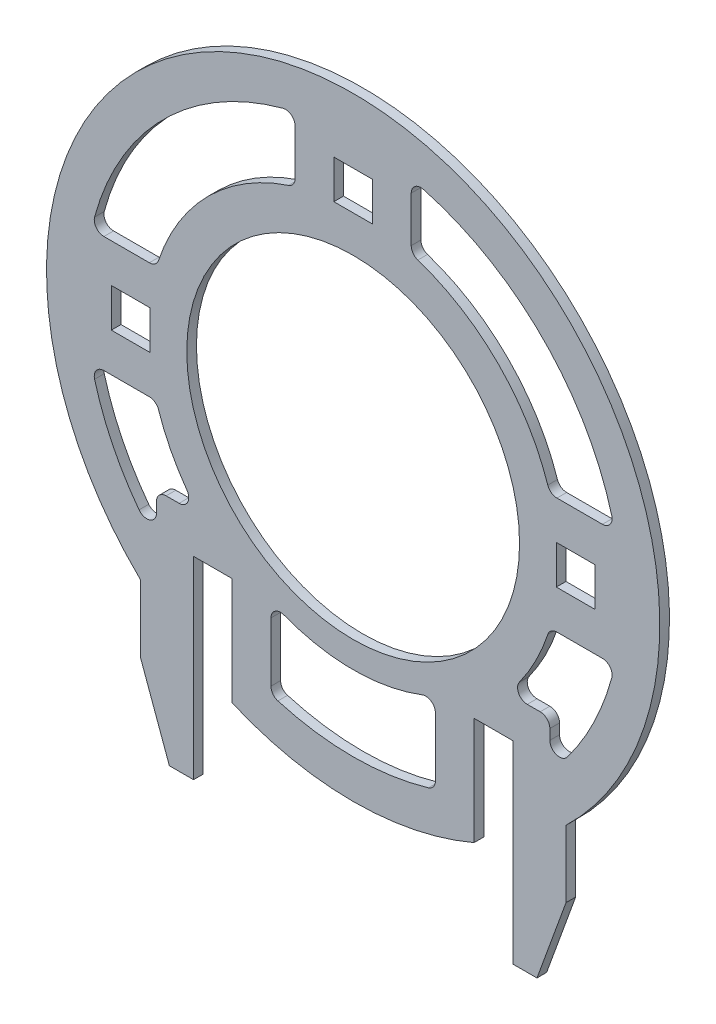
SolidWorks part; units mm, degrees
ref_plane "Plan de face" through (0, 0, 0) normal (0, 0, 1) x (1, 0, 0)
ref_plane "Plan de dessus" through (0, 0, 0) normal (0, 1, 0) x (1, 0, 0)
ref_plane "Plan de droite" through (0, 0, 0) normal (1, 0, 0) x (0, 0, -1)
sketch "Esquisse1" plane through (0, 0, 0) normal (0, 0, 1) x (1, 0, 0)
  line L0 (0, 195) -> (0, 0) construction
  line L1 (0, 0) -> (0, -220) construction
  line L2 (220, -228.2301) -> (220, -297.5757)
  line L3 (190, -380) -> (165, -380)
  line L4 (165, -380) -> (165, -180)
  line L5 (165, -180) -> (125, -180)
  line L6 (125, -180) -> (125, -291.3143)
  line L7 (250, 20) -> (250, -20)
  line L8 (0, -220) -> (0, -317) construction
  line L9 (-220, -228.2301) -> (-220, -297.5757)
  line L10 (-190, -380) -> (-165, -380)
  line L11 (-165, -380) -> (-165, -180)
  line L12 (-165, -180) -> (-125, -180)
  line L13 (-125, -180) -> (-125, -291.3143)
  line L14 (220, -297.5757) -> (190, -380)
  line L15 (-220, -297.5757) -> (-190, -380)
  line L16 (220, 0) -> (-220, 0) construction
  line L17 (270.4237, 60) -> (203.3322, 60)
  line L18 (60, 270.4237) -> (60, 203.3322)
  line L19 (-60, 270.4237) -> (-60, 203.3322)
  line L20 (-270.4237, 60) -> (-203.3322, 60)
  line L21 (203.3322, -60) -> (270.4237, -60)
  line L22 (203.3322, -188.109) -> (203.3322, -140)
  line L23 (210, 20) -> (210, -20)
  line L24 (250, -20) -> (210, -20)
  line L25 (-250, 20) -> (-250, -20)
  line L26 (-20, 250) -> (20, 250)
  line L27 (-20, 250) -> (-20, 210)
  line L28 (-20, 210) -> (20, 210)
  line L29 (20, 250) -> (20, 210)
  line L30 (-85, -180) -> (-85, -263.6361)
  line L31 (85, -180) -> (85, -263.6361)
  line L32 (203.3322, -140) -> (159.198, -140)
  line L33 (-203.3322, -60) -> (-270.4237, -60)
  line L34 (-203.3322, -140) -> (-159.198, -140)
  line L35 (250, 20) -> (210, 20)
  line L36 (-203.3322, -188.109) -> (-203.3322, -140)
  line L45 (-210, -20) -> (-210, 20)
  line L46 (-250, 20) -> (-210, 20)
  line L53 (-250, -20) -> (-210, -20)
  line L57 (20, -250) -> (20, -210) [skipped]
  line L60 (-20, -250) -> (-20, -210) [skipped]
  line L62 (20, -210) -> (-20, -210) [skipped]
  arc A0 (270.4237, 60) -> (60, 270.4237) centre (0, 0) ccw
  arc A1 (203.3322, 60) -> (60, 203.3322) centre (0, 0) ccw
  arc A2 (-203.3322, 60) -> (-60, 203.3322) centre (0, 0) cw
  circle A3 centre (0, 0) radius 172
  arc A4 (-270.4237, 60) -> (-60, 270.4237) centre (0, 0) cw
  arc A5 (220, -228.2301) -> (-220, -228.2301) centre (0, 0) ccw
  arc A6 (-85, -263.6361) -> (85, -263.6361) centre (0, 0) ccw
  arc A7 (-85, -180) -> (85, -180) centre (0, 0) ccw
  arc A8 (203.3322, -60) -> (159.198, -140) centre (0, 0) cw
  arc A9 (270.4237, -60) -> (203.3322, -188.109) centre (0, 0) cw
  arc A10 (-203.3322, -60) -> (-159.198, -140) centre (0, 0) ccw
  arc A11 (-270.4237, -60) -> (-203.3322, -188.109) centre (0, 0) ccw
  arc A29 (-125, -291.3143) -> (125, -291.3143) centre (0, 0) ccw
  point P9 (220, -380)
  point P54 (0, 0)
  point P60 (-220, -380)
  point P78 (207.8614, 0)
  point P79 (-201.9645, 0)
  point P84 (0, 210)
  point P118 (0, 0)
  dimension "D3" = 440
  dimension "D4" = 344
  dimension "D25" = 634
  dimension "D16" = 40
  dimension "D18" = 40
  dimension "D24" = 40
  dimension "D27" = 40
  dimension "D6" = 40
  dimension "D7" = 330
  dimension "D8" = 200
  dimension "D9" = 40
  dimension "D10" = 30
  dimension "D11" = 70
  dimension "D12" = 30
  dimension "D13" = 70
  dimension "D14" = 210
  dimension "D15" = 40
  dimension "D17" = 4
  dimension "D19" = 40
  dimension "D20" = 20
  dimension "D21" = 210
  dimension "D22" = 180
  dimension "D5" = 40
  dimension "D26" = 40
  dimension "D28" = 40
  dimension "D23" = 40
extrude "Boss.-Extru.1" add sketch "Esquisse1" along normal blind 10
fillet "Congé1" radius 10 22 edges at (203.3322, -188.109, 5) (203.3322, -140, 5) (159.198, -140, 5) (203.3322, -60, 5) (270.4237, -60, 5) (85, -180, 5) (85, -263.6361, 5) (-85, -263.6361, 5) (-85, -180, 5) (-203.3322, -60, 5) (-270.4237, -60, 5) (-203.3322, -188.109, 5) (-203.3322, -140, 5) (-159.198, -140, 5) (203.3322, 60, 5) (270.4237, 60, 5) (-203.3322, 60, 5) (-60, 203.3322, 5) (-60, 270.4237, 5) (-270.4237, 60, 5) (60, 203.3322, 5) (60, 270.4237, 5)
